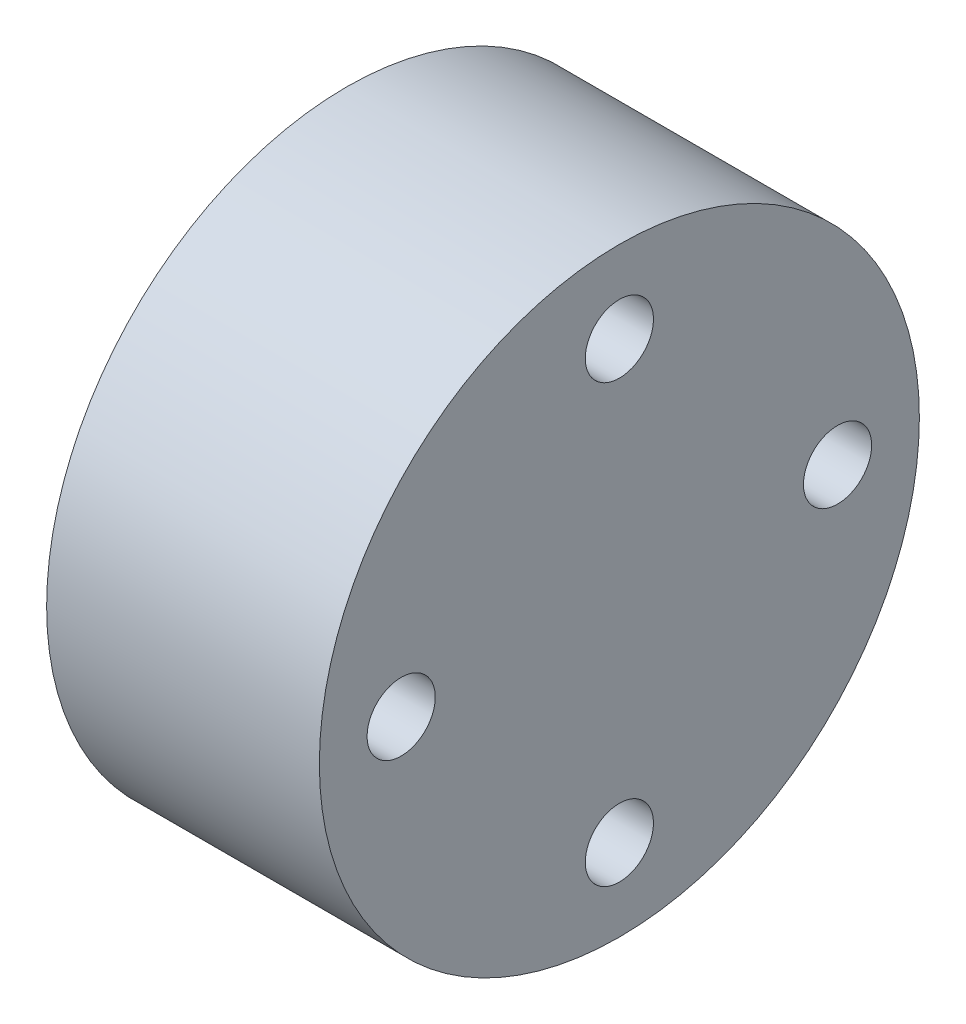
SolidWorks part; units mm, degrees
ref_plane "Front Plane" through (0, 0, 0) normal (0, 0, 1) x (1, 0, 0)
ref_plane "Top Plane" through (0, 0, 0) normal (0, 1, 0) x (1, 0, 0)
ref_plane "Right Plane" through (0, 0, 0) normal (1, 0, 0) x (0, 0, -1)
sketch "Sketch1" plane through (0, 0, 0) normal (1, 0, 0) x (0, 0, -1)
  circle A0 centre (0, 0) radius 11
  dimension "D1" = 22
extrude "Boss-Extrude1" add sketch "Sketch1" along normal blind 10
sketch "Sketch2" plane through (0, 0, 0) normal (-1, 0, 0) x (0, 0, 1)
  circle A0 centre (0, 8) radius 1.25
  circle A1 centre (8, 0) radius 1.25
  circle A2 centre (0, -8) radius 1.25
  circle A3 centre (-8, 0) radius 1.25
  point P11 (0, 0)
  dimension "D1" = 2.5
  dimension "D2" = 8
  dimension "D3" = 4
extrude "Cut-Extrude1" cut sketch "Sketch2" against normal blind 10
sketch "Sketch3" plane through (0, 0, 0) normal (-1, 0, 0) x (0, 0, 1)
  circle A0 centre (0, 0) radius 5
  dimension "D1" = 10
extrude "Cut-Extrude2" cut sketch "Sketch3" against normal blind 5
